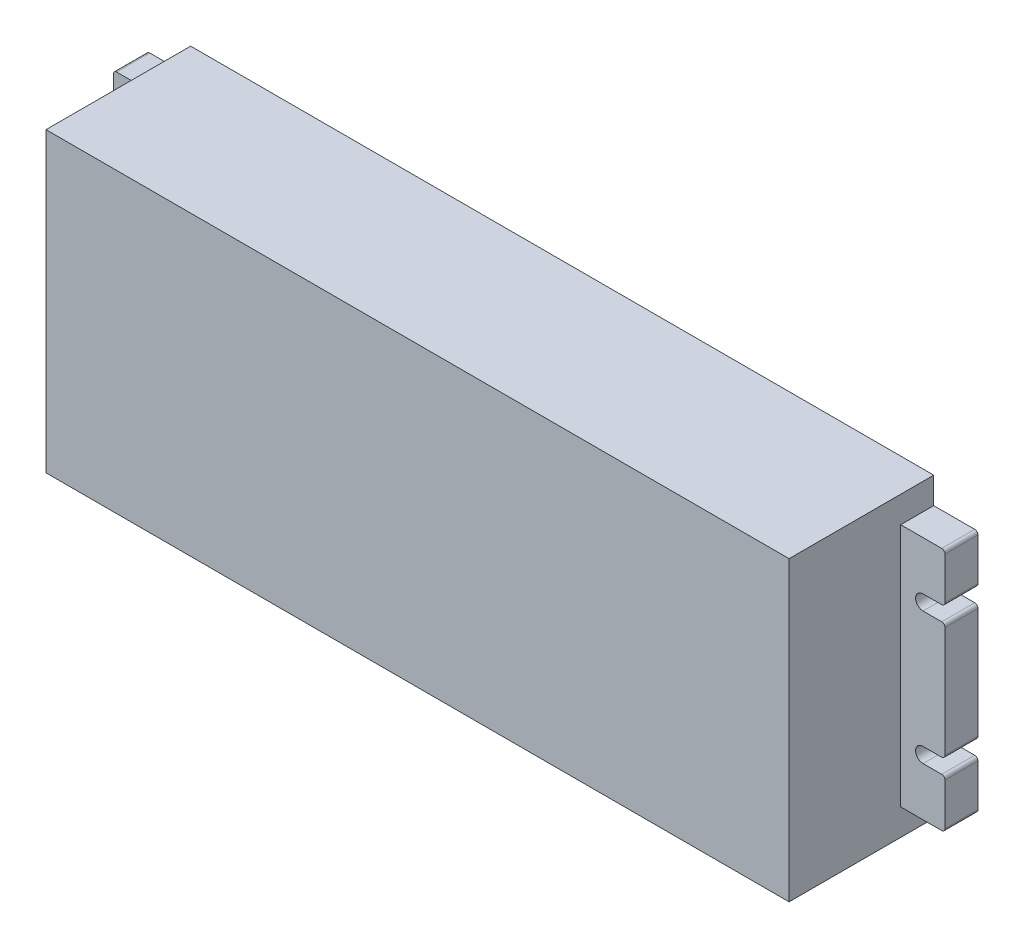
SolidWorks part; units mm, degrees
ref_plane "Front" through (0, 0, 0) normal (0, 0, 1) x (1, 0, 0)
ref_plane "Top" through (0, 0, 0) normal (0, 1, 0) x (1, 0, 0)
ref_plane "Right" through (0, 0, 0) normal (1, 0, 0) x (0, 0, -1)
sketch "Sketch1" plane through (0, 0, 0) normal (0, 0, 1) x (1, 0, 0)
  line L1 (-112.5, -45) -> (112.5, -45)
  line L2 (-112.5, -45) -> (-112.5, 45)
  line L3 (-112.5, 45) -> (112.5, 45)
  line L4 (112.5, -45) -> (112.5, 45)
  line L5 (-112.5, -45) -> (112.5, 45) construction
  line L6 (-112.5, 45) -> (112.5, -45) construction
  point P0 (0, 0)
  dimension "D1" = 225
  dimension "D2" = 90
extrude "Boss-Extrude1" add sketch "Sketch1" along normal blind 43.8
sketch "Sketch2" plane through (0, 0, 0) normal (0, 0, 1) x (1, 0, 0)
  line L0 (-112.5, 45) -> (-112.5, -45) construction
  line L1 (-112.5, 37) -> (-124.9, 37)
  line L2 (-112.5, 37) -> (-112.5, -37)
  line L3 (-112.5, -37) -> (-124.9, -37)
  line L4 (-125.9, 36) -> (-125.9, 23.25)
  line L5 (-112.5, 0) -> (-126, 0) construction
  line L6 (-119.25, -20) -> (-119.25, 20) construction
  line L7 (-119.25, 22.25) -> (-124.9, 22.25)
  line L8 (-119.25, 17.75) -> (-124.9, 17.75)
  line L9 (-119.25, -17.75) -> (-124.9, -17.75)
  line L10 (-119.25, -22.25) -> (-124.9, -22.25)
  line L11 (-125.9, 16.75) -> (-125.9, -16.75)
  line L12 (-125.9, -23.25) -> (-125.9, -36)
  line L13 (-117, -20) -> (-117, 20) construction
  arc A0 (-119.25, 17.75) -> (-119.25, 22.25) centre (-119.25, 20) ccw
  arc A1 (-119.25, -22.25) -> (-119.25, -17.75) centre (-119.25, -20) ccw
  arc A2 (-124.9, -37) -> (-125.9, -36) centre (-124.9, -36) cw
  arc A3 (-124.9, -22.25) -> (-125.9, -23.25) centre (-124.9, -23.25) ccw
  arc A4 (-124.9, -17.75) -> (-125.9, -16.75) centre (-124.9, -16.75) cw
  arc A5 (-124.9, 17.75) -> (-125.9, 16.75) centre (-124.9, 16.75) ccw
  arc A6 (-124.9, 22.25) -> (-125.9, 23.25) centre (-124.9, 23.25) cw
  arc A7 (-124.9, 37) -> (-125.9, 36) centre (-124.9, 36) ccw
  point P6 (-112.5, 0)
  point P7 (-112.5, 0)
  point P13 (-119.25, 0)
  point P14 (-116.95, -20)
  point P24 (-117, 0)
  point P25 (0, 0)
  point P28 (-125.9, -37)
  point P31 (-125.9, -22.25)
  point P36 (-125.9, 17.75)
  point P41 (-125.9, 37)
  dimension "D4" = 4.5
  dimension "D6" = 1
  dimension "D1" = 74
  dimension "D2" = 13.4
  dimension "D3" = 40
  dimension "D5" = 8.9
extrude "Boss-Extrude2" add sketch "Sketch2" along normal blind 10
mirror "Mirror1" about plane through (0, 0, 0) normal (1, 0, 0) of "Boss-Extrude2"
